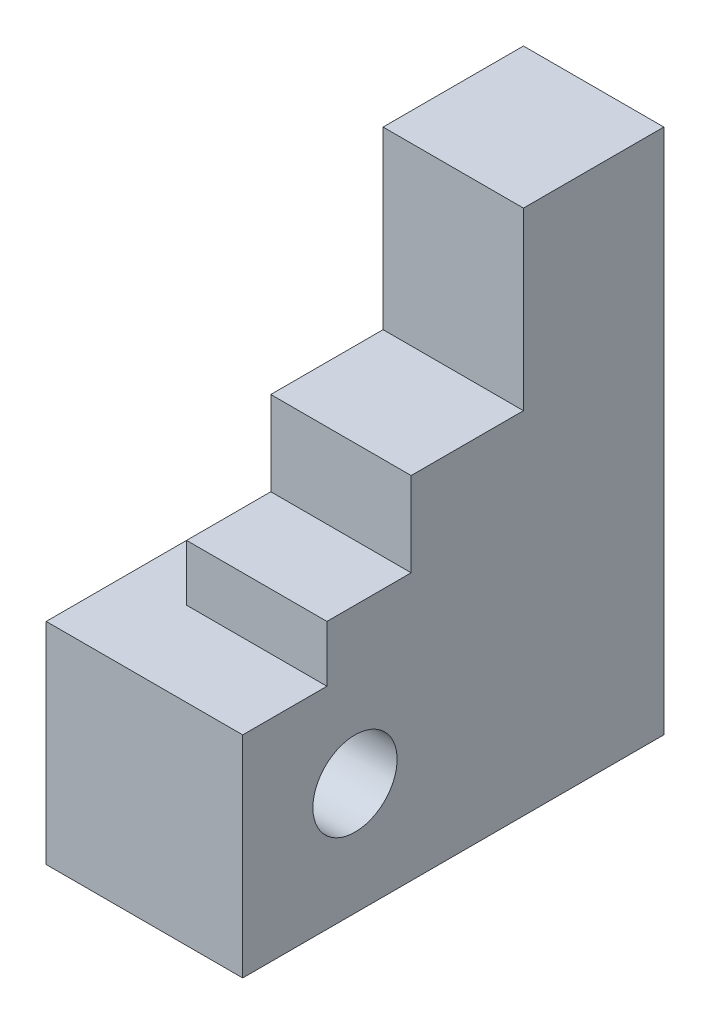
SolidWorks part; units mm, degrees
ref_plane "Front Plane" through (0, 0, 0) normal (0, 0, 1) x (1, 0, 0)
ref_plane "Top Plane" through (0, 0, 0) normal (0, 1, 0) x (1, 0, 0)
ref_plane "Right Plane" through (0, 0, 0) normal (1, 0, 0) x (0, 0, -1)
sketch "Sketch1" plane through (0, 0, 0) normal (0, 1, 0) x (1, 0, 0)
  line L1 (-14, 30) -> (14, 30)
  line L2 (-14, 30) -> (-14, -30)
  line L3 (-14, -30) -> (14, -30)
  line L4 (14, 30) -> (14, -30)
  line L5 (-14, 30) -> (14, -30) construction
  line L6 (-14, -30) -> (14, 30) construction
  point P0 (0, 0)
  dimension "D1" = 60
  dimension "D2" = 28
extrude "Boss-Extrude1" add sketch "Sketch1" along normal blind 30
sketch "Sketch3" plane through (0, 30, 0) normal (0, 1, 0) x (1, 0, 0)
  line L1 (14, 30) -> (-6, 30)
  line L2 (14, 30) -> (14, -18)
  line L3 (14, -18) -> (-6, -18)
  line L4 (-6, 30) -> (-6, -18)
  dimension "D1" = 48
  dimension "D2" = 20
extrude "Boss-Extrude2" add sketch "Sketch3" along normal blind 8
sketch "Sketch4" plane through (0, 38, 0) normal (0, 1, 0) x (1, 0, 0)
  line L0 (-6, 30) -> (-6, -18) construction
  line L1 (14, 30) -> (-6, 30)
  line L2 (14, 30) -> (14, -6)
  line L3 (14, -6) -> (-6, -6)
  line L4 (-6, 30) -> (-6, -6)
  dimension "D1" = 36
extrude "Boss-Extrude3" add sketch "Sketch4" along normal blind 12
sketch "Sketch5" plane through (0, 50, 0) normal (0, 1, 0) x (1, 0, 0)
  line L0 (-6, 30) -> (-6, -6) construction
  line L1 (14, 30) -> (-6, 30)
  line L2 (14, 30) -> (14, 10)
  line L3 (14, 10) -> (-6, 10)
  line L4 (-6, 30) -> (-6, 10)
  dimension "D1" = 20
extrude "Boss-Extrude4" add sketch "Sketch5" along normal blind 25
sketch "Sketch6" plane through (-14, 0, 0) normal (-1, 0, 0) x (0, 0, 1)
  line L0 (14, 16) -> (14, 0) construction
  line L1 (-30, 0) -> (30, 0) construction
  line L2 (14, 0) -> (14, 16) construction
  line L3 (14, 16) -> (30, 16) construction
  line L4 (30, 30) -> (30, 0) construction
  line L5 (-30, 30) -> (-30, 0) construction
  line L6 (-10, 50) -> (6, 50) construction
  line L7 (-30, 30) -> (18, 30) construction
  line L8 (-30, 75) -> (-10, 75) construction
  line L9 (6, 38) -> (18, 38) construction
  circle A0 centre (14, 16) radius 6
  dimension "D3" = 12
  dimension "D1" = 16
  dimension "D2" = 16
  dimension "D4" = 30
  dimension "D5" = 20
  dimension "D6" = 75
  dimension "D7" = 12
extrude "Cut-Extrude1" cut sketch "Sketch6" against normal blind 35
